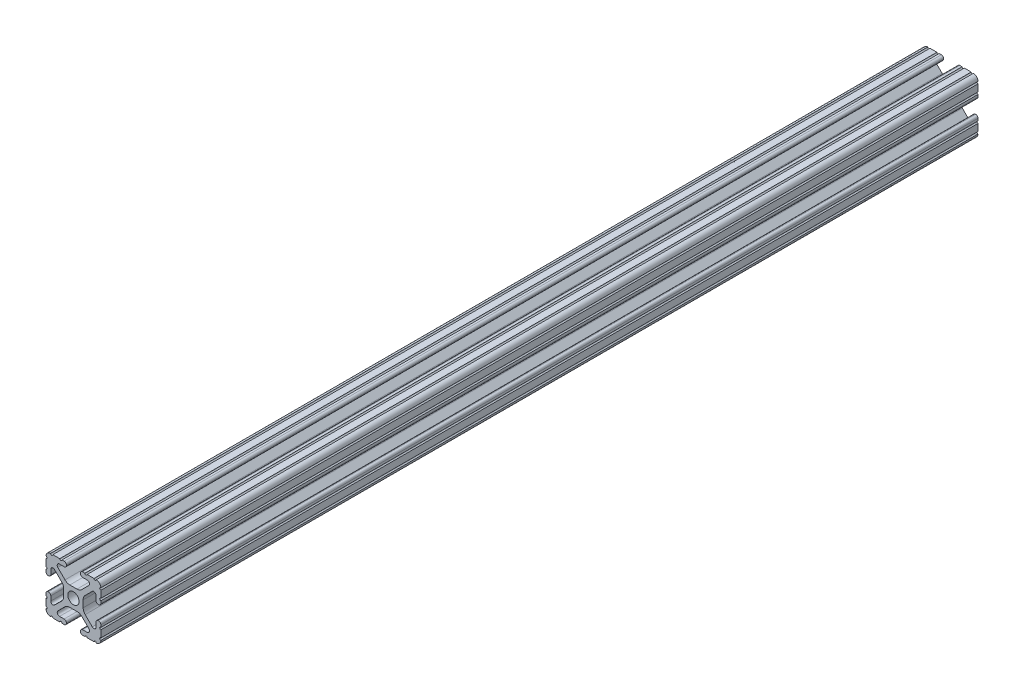
SolidWorks part; units mm, degrees
ref_plane "Front Plane" through (0, 0, 0) normal (0, 0, 1) x (1, 0, 0)
ref_plane "Top Plane" through (0, 0, 0) normal (0, 1, 0) x (1, 0, 0)
ref_plane "Right Plane" through (0, 0, 0) normal (1, 0, 0) x (0, 0, -1)
sketch "Sketch1" plane through (0, 0, 0) normal (0, 0, 1) x (1, 0, 0)
  line L88 (-7.1797, -8.6452) -> (-3.9523, -5.4237)
  line L89 (-1.7093, -4.4958) -> (1.7093, -4.4958)
  line L90 (3.9523, -5.4237) -> (7.1797, -8.6452)
  line L91 (6.4164, -10.4902) -> (4.2875, -10.4902)
  line L92 (3.2385, -11.5392) -> (3.2385, -11.651)
  line L93 (4.2875, -12.7) -> (5.3171, -12.7)
  line L94 (6.3331, -12.7) -> (9.5504, -12.7)
  line L95 (12.7, -9.5504) -> (12.7, -6.3331)
  line L96 (12.7, -5.3171) -> (12.7, -4.2875)
  line L97 (11.651, -3.2385) -> (11.5392, -3.2385)
  line L98 (10.4902, -4.2875) -> (10.4902, -6.4021)
  line L99 (8.7371, -7.1294) -> (5.441, -3.8408)
  line L100 (4.5085, -1.5932) -> (4.5085, 1.5932)
  line L101 (5.441, 3.8408) -> (8.7371, 7.1294)
  line L102 (10.4902, 6.4021) -> (10.4902, 4.2875)
  line L103 (11.5392, 3.2385) -> (11.651, 3.2385)
  line L104 (12.7, 4.2875) -> (12.7, 5.3171)
  line L105 (12.7, 6.3331) -> (12.7, 9.5504)
  line L106 (9.5504, 12.7) -> (6.3331, 12.7)
  line L107 (5.3171, 12.7) -> (4.2875, 12.7)
  line L108 (3.2385, 11.651) -> (3.2385, 11.5392)
  line L109 (4.2875, 10.4902) -> (6.4768, 10.4902)
  line L110 (7.207, 8.7244) -> (3.8983, 5.4232)
  line L111 (1.6558, 4.4958) -> (-1.6558, 4.4958)
  line L112 (-3.8983, 5.4232) -> (-7.207, 8.7244)
  line L113 (-6.4768, 10.4902) -> (-4.2875, 10.4902)
  line L114 (-3.2385, 11.5392) -> (-3.2385, 11.651)
  line L115 (-4.2875, 12.7) -> (-5.3171, 12.7)
  line L116 (-6.3331, 12.7) -> (-9.5504, 12.7)
  line L117 (-12.7, 9.5504) -> (-12.7, 6.3331)
  line L118 (-12.7, 5.3171) -> (-12.7, 4.2875)
  line L119 (-11.651, 3.2385) -> (-11.5392, 3.2385)
  line L120 (-10.4902, 4.2875) -> (-10.4902, 6.4021)
  line L121 (-8.7371, 7.1294) -> (-5.441, 3.8408)
  line L122 (-4.5085, 1.5932) -> (-4.5085, -1.5932)
  line L123 (-5.441, -3.8408) -> (-8.7371, -7.1294)
  line L124 (-10.4902, -6.4021) -> (-10.4902, -4.2875)
  line L125 (-11.5392, -3.2385) -> (-11.651, -3.2385)
  line L126 (-12.7, -4.2875) -> (-12.7, -5.3171)
  line L127 (-12.7, -6.3331) -> (-12.7, -9.5504)
  line L128 (-9.5504, -12.7) -> (-6.3331, -12.7)
  line L129 (-5.3171, -12.7) -> (-4.2875, -12.7)
  line L130 (-3.2385, -11.651) -> (-3.2385, -11.5392)
  line L131 (-4.2875, -10.4902) -> (-6.4164, -10.4902)
  circle A1 centre (0, 0) radius 2.6035
  arc A104 (-7.1797, -8.6452) -> (-6.4164, -10.4902) centre (-6.4164, -9.4098) ccw
  arc A105 (-1.7093, -4.4958) -> (-3.9523, -5.4237) centre (-1.7093, -7.6708) ccw
  arc A106 (3.9523, -5.4237) -> (1.7093, -4.4958) centre (1.7093, -7.6708) ccw
  arc A107 (6.4164, -10.4902) -> (7.1797, -8.6452) centre (6.4164, -9.4098) ccw
  arc A108 (4.2875, -10.4902) -> (3.2385, -11.5392) centre (4.2875, -11.5392) ccw
  arc A109 (3.2385, -11.651) -> (4.2875, -12.7) centre (4.2875, -11.651) ccw
  arc A110 (6.3331, -12.7) -> (5.3171, -12.7) centre (5.8251, -12.7) ccw
  arc A111 (10.5664, -12.6998) -> (9.5504, -12.7) centre (10.0584, -12.7) ccw
  arc A112 (10.5664, -12.6998) -> (12.6998, -10.5664) centre (10.5918, -10.5918) ccw
  arc A113 (12.7, -9.5504) -> (12.6998, -10.5664) centre (12.7, -10.0584) ccw
  arc A114 (12.7, -5.3171) -> (12.7, -6.3331) centre (12.7, -5.8251) ccw
  arc A115 (12.7, -4.2875) -> (11.651, -3.2385) centre (11.651, -4.2875) ccw
  arc A116 (11.5392, -3.2385) -> (10.4902, -4.2875) centre (11.5392, -4.2875) ccw
  arc A117 (8.7371, -7.1294) -> (10.4902, -6.4021) centre (9.4628, -6.4021) ccw
  arc A118 (4.5085, -1.5932) -> (5.441, -3.8408) centre (7.6835, -1.5932) ccw
  arc A119 (5.441, 3.8408) -> (4.5085, 1.5932) centre (7.6835, 1.5932) ccw
  arc A120 (10.4902, 6.4021) -> (8.7371, 7.1294) centre (9.4628, 6.4021) ccw
  arc A121 (10.4902, 4.2875) -> (11.5392, 3.2385) centre (11.5392, 4.2875) ccw
  arc A122 (11.651, 3.2385) -> (12.7, 4.2875) centre (11.651, 4.2875) ccw
  arc A123 (12.7, 6.3331) -> (12.7, 5.3171) centre (12.7, 5.8251) ccw
  arc A124 (12.6998, 10.5664) -> (12.7, 9.5504) centre (12.7, 10.0584) ccw
  arc A125 (12.6998, 10.5664) -> (10.5664, 12.6998) centre (10.5918, 10.5918) ccw
  arc A126 (9.5504, 12.7) -> (10.5664, 12.6998) centre (10.0584, 12.7) ccw
  arc A127 (5.3171, 12.7) -> (6.3331, 12.7) centre (5.8251, 12.7) ccw
  arc A128 (4.2875, 12.7) -> (3.2385, 11.651) centre (4.2875, 11.651) ccw
  arc A129 (3.2385, 11.5392) -> (4.2875, 10.4902) centre (4.2875, 11.5392) ccw
  arc A130 (7.207, 8.7244) -> (6.4768, 10.4902) centre (6.4768, 9.4563) ccw
  arc A131 (1.6558, 4.4958) -> (3.8983, 5.4232) centre (1.6558, 7.6708) ccw
  arc A132 (-3.8983, 5.4232) -> (-1.6558, 4.4958) centre (-1.6558, 7.6708) ccw
  arc A133 (-6.4768, 10.4902) -> (-7.207, 8.7244) centre (-6.4768, 9.4563) ccw
  arc A134 (-4.2875, 10.4902) -> (-3.2385, 11.5392) centre (-4.2875, 11.5392) ccw
  arc A135 (-3.2385, 11.651) -> (-4.2875, 12.7) centre (-4.2875, 11.651) ccw
  arc A136 (-6.3331, 12.7) -> (-5.3171, 12.7) centre (-5.8251, 12.7) ccw
  arc A137 (-10.5664, 12.6998) -> (-9.5504, 12.7) centre (-10.0584, 12.7) ccw
  arc A138 (-10.5664, 12.6998) -> (-12.6998, 10.5664) centre (-10.5918, 10.5918) ccw
  arc A139 (-12.7, 9.5504) -> (-12.6998, 10.5664) centre (-12.7, 10.0584) ccw
  arc A140 (-12.7, 5.3171) -> (-12.7, 6.3331) centre (-12.7, 5.8251) ccw
  arc A141 (-12.7, 4.2875) -> (-11.651, 3.2385) centre (-11.651, 4.2875) ccw
  arc A142 (-11.5392, 3.2385) -> (-10.4902, 4.2875) centre (-11.5392, 4.2875) ccw
  arc A143 (-8.7371, 7.1294) -> (-10.4902, 6.4021) centre (-9.4628, 6.4021) ccw
  arc A144 (-4.5085, 1.5932) -> (-5.441, 3.8408) centre (-7.6835, 1.5932) ccw
  arc A145 (-5.441, -3.8408) -> (-4.5085, -1.5932) centre (-7.6835, -1.5932) ccw
  arc A146 (-10.4902, -6.4021) -> (-8.7371, -7.1294) centre (-9.4628, -6.4021) ccw
  arc A147 (-10.4902, -4.2875) -> (-11.5392, -3.2385) centre (-11.5392, -4.2875) ccw
  arc A148 (-11.651, -3.2385) -> (-12.7, -4.2875) centre (-11.651, -4.2875) ccw
  arc A149 (-12.7, -6.3331) -> (-12.7, -5.3171) centre (-12.7, -5.8251) ccw
  arc A150 (-12.6998, -10.5664) -> (-12.7, -9.5504) centre (-12.7, -10.0584) ccw
  arc A151 (-12.6998, -10.5664) -> (-10.5664, -12.6998) centre (-10.5918, -10.5918) ccw
  arc A152 (-9.5504, -12.7) -> (-10.5664, -12.6998) centre (-10.0584, -12.7) ccw
  arc A153 (-5.3171, -12.7) -> (-6.3331, -12.7) centre (-5.8251, -12.7) ccw
  arc A154 (-4.2875, -12.7) -> (-3.2385, -11.651) centre (-4.2875, -11.651) ccw
  arc A155 (-3.2385, -11.5392) -> (-4.2875, -10.4902) centre (-4.2875, -11.5392) ccw
extrude "Boss-Extrude1" add sketch "Sketch1" along normal mid plane 406.4
